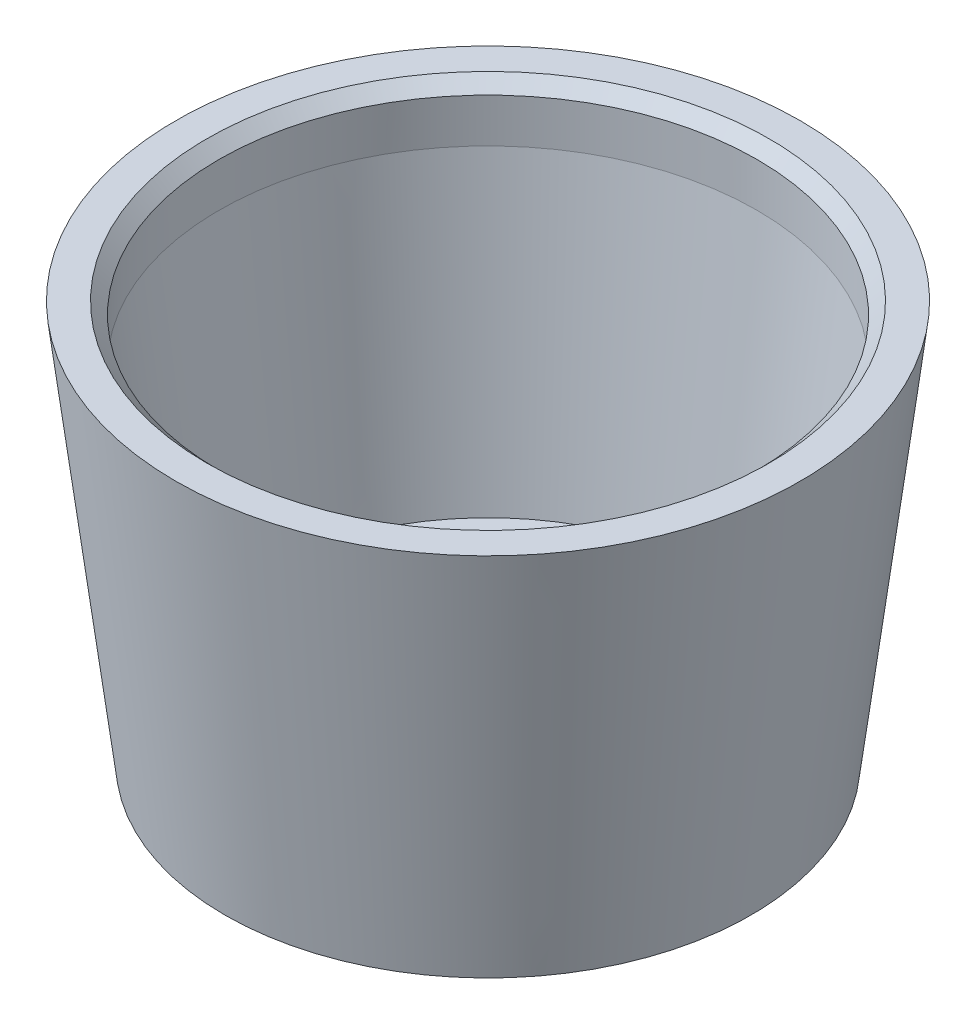
SolidWorks part; units mm, degrees
material "6061 Alloy"
ref_plane "Front Plane" through (0, 0, 0) normal (0, 0, 1) x (1, 0, 0)
ref_plane "Top Plane" through (0, 0, 0) normal (0, 1, 0) x (1, 0, 0)
ref_plane "Right Plane" through (0, 0, 0) normal (1, 0, 0) x (0, 0, -1)
sketch "Sketch1" plane through (0, 0, 0) normal (1, 0, 0) x (0, 0, -1)
  line L0 (0, 0) -> (41.7332, 0) construction
  line L1 (41.7332, 0) -> (49.53, 63.5)
  line L2 (49.53, 63.5) -> (42.6805, 63.5)
  line L3 (42.6805, 63.5) -> (42.6805, 54.61)
  line L5 (42.6805, 54.61) -> (36.9109, 7.62)
  line L6 (36.9109, 7.62) -> (0, 7.62)
  line L8 (0, 0) -> (0, 78.9879) construction
  line L9 (36.9109, 7.62) -> (36.9109, 24.8426) construction
  line L10 (41.7332, 0) -> (36.6532, 0)
  line L11 (36.6532, 0) -> (36.0182, 0.635)
  line L12 (36.0182, 0.635) -> (0, 0.635)
  line L13 (0, 0.635) -> (0, 7.62)
  line L14 (36.6532, 0) -> (36.6532, 5.2523) construction
  point P9 (32.9887, 26.7476)
  point P16 (0, 0)
  point P17 (0, 0)
  dimension "D2" = 7.62
  dimension "D3" = 49.53
  dimension "D4" = 7
  dimension "D5" = 5.715
  dimension "D6" = 8.89
  dimension "D7" = 63.5
  dimension "D8" = 1.27
  dimension "D9" = 45
  dimension "D10" = 5.08
revolve "Revolve1" add sketch "Sketch1" angle 360 about L8
chamfer "Chamfer1" distance 1.905 angle 45 1 edges at (0, 63.5, -42.6805)
